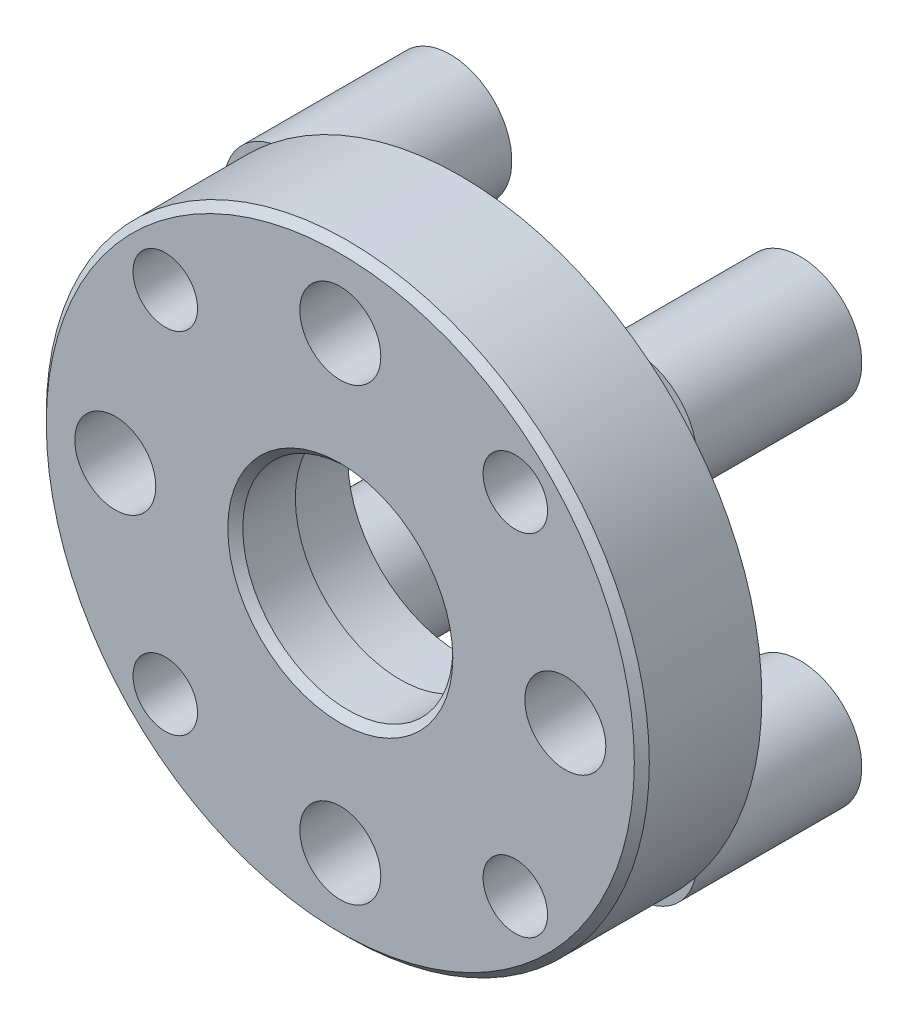
SolidWorks part; units mm, degrees
material "ABS"
ref_plane "Front Plane" through (0, 0, 0) normal (0, 0, 1) x (1, 0, 0)
ref_plane "Top Plane" through (0, 0, 0) normal (0, 1, 0) x (1, 0, 0)
ref_plane "Right Plane" through (0, 0, 0) normal (1, 0, 0) x (0, 0, -1)
ref_plane "Output Plane" through (0, 0, 23.2347) normal (0, 0, -1) x (-1, 0, 0)
sketch "CYC Output Sketch" plane through (0, 0, 23.2347) normal (0, 0, 1) x (1, 0, 0)
  line L1 (11.6673, 11.6673) -> (-11.6673, 11.6673) construction
  line L2 (-11.6673, 11.6673) -> (-11.6673, -11.6673) construction
  line L3 (-11.6673, -11.6673) -> (11.6673, -11.6673) construction
  line L4 (11.6673, -11.6673) -> (11.6673, 11.6673) construction
  circle A0 centre (0, 0) radius 16.5 construction
sketch "Sketch3" plane through (0, 0, 23.2347) normal (0, 0, -1) x (-1, 0, 0)
  circle A0 centre (-11.6673, 11.6673) radius 4
  circle A1 centre (11.6673, 11.6673) radius 4
  circle A2 centre (11.6673, -11.6673) radius 4
  circle A3 centre (-11.6673, -11.6673) radius 4
  dimension "D1" = 8
extrude "Boss-Extrude1" add sketch "Sketch3" along normal blind 11
sketch "Sketch6" plane through (0, 0, 23.2347) normal (0, 0, 1) x (1, 0, 0)
  arc A0 (10.7357, 16.9928) -> (-16.9928, 10.7357) centre (0, 0) ccw
  arc A18 (16.9928, -10.7357) -> (10.7357, 16.9928) centre (0, 0) ccw
  arc A19 (-10.7357, -16.9928) -> (16.9928, -10.7357) centre (0, 0) ccw
  arc A20 (-16.9928, 10.7357) -> (-10.7357, -16.9928) centre (0, 0) ccw
  circle A23 centre (0, 0) radius 7.5
  dimension "D2" = 40.2
  dimension "D1" = 15
extrude "Boss-Extrude6" add sketch "Sketch6" along normal blind 8 contours A23 | A0 A20 A19 A18
sketch "Sketch8" plane through (0, 0, 31.2347) normal (0, 0, 1) x (1, 0, 0)
  line L0 (0, 0) -> (11.6673, 11.6673) construction
  line L1 (0, 0) -> (16.5, 0) construction
  circle A0 centre (0, 0) radius 16.5 construction
  circle A1 centre (11.6673, 11.6673) radius 1.6
  circle A2 centre (11.6673, -11.6673) radius 1.6
  circle A3 centre (-11.6673, -11.6673) radius 1.6
  circle A4 centre (-11.6673, 11.6673) radius 1.6
  point P16 (0, 0)
  dimension "D1" = 33
  dimension "D2" = 45
  dimension "D3" = 3.2
  dimension "D4" = 4
extrude "Cut-Extrude1" cut sketch "Sketch8" against normal through all
sketch "Sketch9" plane through (0, 0, 12.2347) normal (0, 0, 1) x (1, 0, 0)
  circle A0 centre (11.6673, 11.6673) radius 3
  circle A1 centre (11.6673, -11.6673) radius 3
  circle A2 centre (-11.6673, -11.6673) radius 3
  circle A3 centre (-11.6673, 11.6673) radius 3
  point P12 (0, 0)
  dimension "D1" = 6
  dimension "D2" = 4
extrude "Cut-Extrude2" cut sketch "Sketch9" along normal blind 3 from surface at 0 starting at face at (13.2673, 11.6673, 12.2347)
sketch "Sketch10" plane through (0, 0, 12.2347) normal (0, 0, -1) x (-1, 0, 0)
  circle A0 centre (11.6673, 11.6673) radius 4.1
  circle A1 centre (11.6673, 11.6673) radius 4
  circle A2 centre (11.6673, -11.6673) radius 4
  circle A3 centre (11.6673, -11.6673) radius 4.1
  circle A4 centre (-11.6673, -11.6673) radius 4
  circle A5 centre (-11.6673, -11.6673) radius 4.1
  circle A6 centre (-11.6673, 11.6673) radius 4
  circle A7 centre (-11.6673, 11.6673) radius 4.1
  point P16 (0, 0)
  dimension "D1" = 8
  dimension "D2" = 8.2
  dimension "D3" = 4
extrude "Boss-Extrude8" add sketch "Sketch10" against normal blind 11
sketch "Sketch11" plane through (0, 0, 31.2347) normal (0, 0, 1) x (1, 0, 0)
  line L0 (0, 0) -> (0, 15) construction
  circle A0 centre (0, 15) radius 2.7
  circle A1 centre (15, 0) radius 2.7
  circle A2 centre (0, -15) radius 2.7
  circle A3 centre (-15, 0) radius 2.7
  circle A4 centre (-11.6673, 11.6673) radius 2.15
  circle A5 centre (11.6673, 11.6673) radius 2.15
  circle A6 centre (11.6673, -11.6673) radius 2.15
  circle A7 centre (-11.6673, -11.6673) radius 2.15
  point P13 (0, 0)
  dimension "D2" = 5.4
  dimension "D4" = 4.3
  dimension "D1" = 15
  dimension "D3" = 4
extrude "Cut-Extrude3" cut sketch "Sketch11" against normal blind 8
sketch "Sketch12" plane through (0, 0, 31.2347) normal (0, 0, 1) x (1, 0, 0)
  circle A0 centre (0, 0) radius 7.5
  circle A1 centre (0, 0) radius 7
  dimension "D1" = 15
  dimension "D2" = 14
extrude "Boss-Extrude9" add sketch "Sketch12" against normal blind 4
chamfer "Chamfer1" distance 0.5 angle 45 2 edges at (7, 0, 31.2347) (20.1, 0, 31.2347)
equation "\"RingPinShaft\"= 5.05"
equation "\"CenterBearingOut\"=32.00"
equation "\"RingPostIn\"=5.15"
equation "\"CamBearingOut\"=15.1"
equation "\"DiskOutputShaft\"=10.1"
equation "\"CenterShaft\"=25.2"
equation "\"Eccentricity\"=2"
equation "\"CycCamShaft\"=10.05"
equation "\"D2@Sketch6\"=\"OutputBearing\""
equation "\"OutputBearing\"=40.2"
